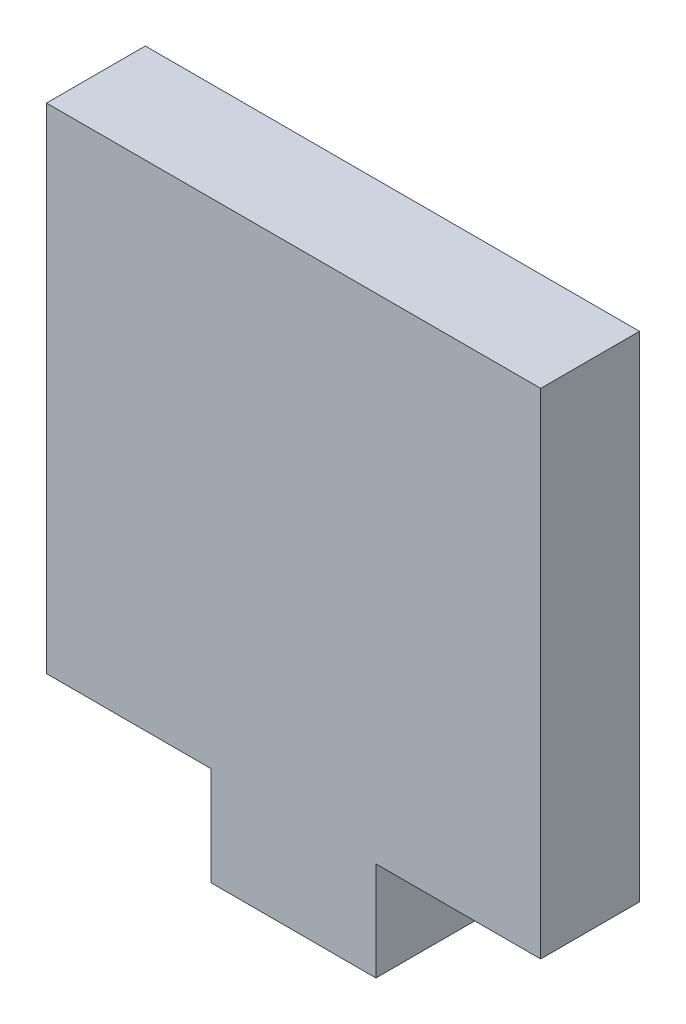
SolidWorks part; units mm, degrees
ref_plane "Front" through (0, 0, 0) normal (0, 0, 1) x (1, 0, 0)
ref_plane "Top" through (0, 0, 0) normal (0, 1, 0) x (1, 0, 0)
ref_plane "Right" through (0, 0, 0) normal (1, 0, 0) x (0, 0, -1)
sketch "草图1" plane through (0, 0, 0) normal (0, 0, 1) x (1, 0, 0)
  line L0 (10, 0) -> (15, 0)
  line L1 (0, 0) -> (5, 0)
  line L2 (0, 0) -> (0, 15)
  line L3 (0, 15) -> (15, 15)
  line L4 (15, 0) -> (15, 15)
  line L6 (5, 0) -> (5, -3)
  line L7 (5, -3) -> (10, -3)
  line L8 (10, 0) -> (10, -3)
  dimension "D1" = 3
  dimension "D2" = 5
  dimension "D3" = 15
  dimension "D4" = 15
  dimension "D5" = 5
extrude "凸台-拉伸1" add sketch "草图1" along normal blind 3
